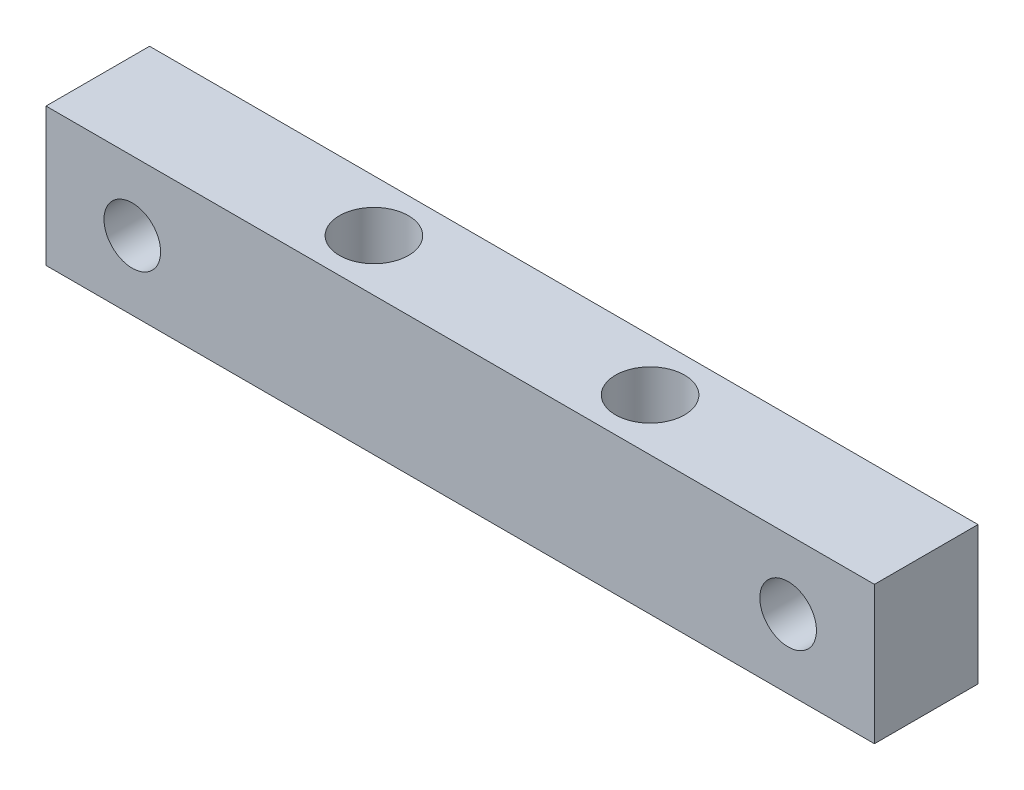
SolidWorks part; units mm, degrees
ref_plane "Front Plane" through (0, 0, 0) normal (0, 0, 1) x (1, 0, 0)
ref_plane "Top Plane" through (0, 0, 0) normal (0, 1, 0) x (1, 0, 0)
ref_plane "Right Plane" through (0, 0, 0) normal (1, 0, 0) x (0, 0, -1)
sketch "Sketch1" plane through (0, 788.1561, 0) normal (0, 1, 0) x (1, 0, 0)
  line L0 (38.1, -152.4) -> (38.1, 76.2) construction
  line L1 (-38.1, 63.5) -> (38.1, 63.5)
  line L2 (-38.1, 63.5) -> (-38.1, 53.975)
  line L3 (-38.1, 53.975) -> (38.1, 53.975)
  line L4 (38.1, 63.5) -> (38.1, 53.975)
  line L5 (-38.1, -152.4) -> (-38.1, 76.2) construction
  line L6 (0, 53.975) -> (0, 63.5) construction
  line L7 (-25.4, 63.5) -> (-25.4, 53.975) construction
  line L8 (0, 53.975) -> (-25.4, 63.5) construction
  line L10 (-38.1, 76.2) -> (38.1, 76.2) construction
  circle A0 centre (-12.7, 58.7375) radius 3.175
  circle A1 centre (12.7, 58.7375) radius 3.175
  dimension "D2" = 6.35
  dimension "D1" = 9.525
  dimension "D3" = 12.7
  dimension "D4" = 12.7
extrude "Boss-Extrude1" add sketch "Sketch1" along normal blind 12.7
sketch "Sketch2" plane through (0, 0, -63.5) normal (0, 0, -1) x (-1, 0, 0)
  circle A0 centre (30.1625, 794.5061) radius 3.175 construction
  circle A1 centre (-30.1625, 794.5061) radius 3.175 construction
  circle A2 centre (30.1625, 794.5061) radius 3.175 construction
  circle A3 centre (-30.1625, 794.5061) radius 3.175 construction
  circle A4 centre (30.1625, 794.5061) radius 2.6035
  circle A5 centre (-30.1625, 794.5061) radius 2.6035
  dimension "D1" = 5.207
extrude "Cut-Extrude1" cut sketch "Sketch2" against normal up to next
